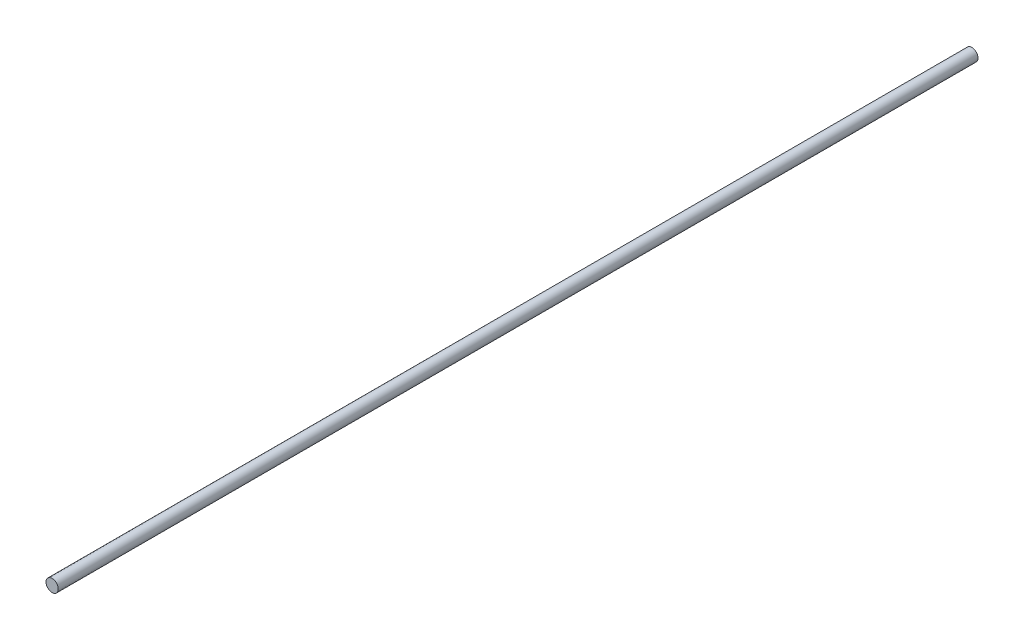
SolidWorks part; units mm, degrees
ref_plane "前视基准面" through (0, 0, 0) normal (0, 0, 1) x (1, 0, 0)
ref_plane "上视基准面" through (0, 0, 0) normal (0, 1, 0) x (1, 0, 0)
ref_plane "右视基准面" through (0, 0, 0) normal (1, 0, 0) x (0, 0, -1)
sketch "草图1" plane through (0, 0, 0) normal (0, 0, 1) x (1, 0, 0)
  circle A0 centre (0, 0) radius 1
  dimension "D1" = 2
extrude "凸台-拉伸1" add sketch "草图1" along normal blind 150
